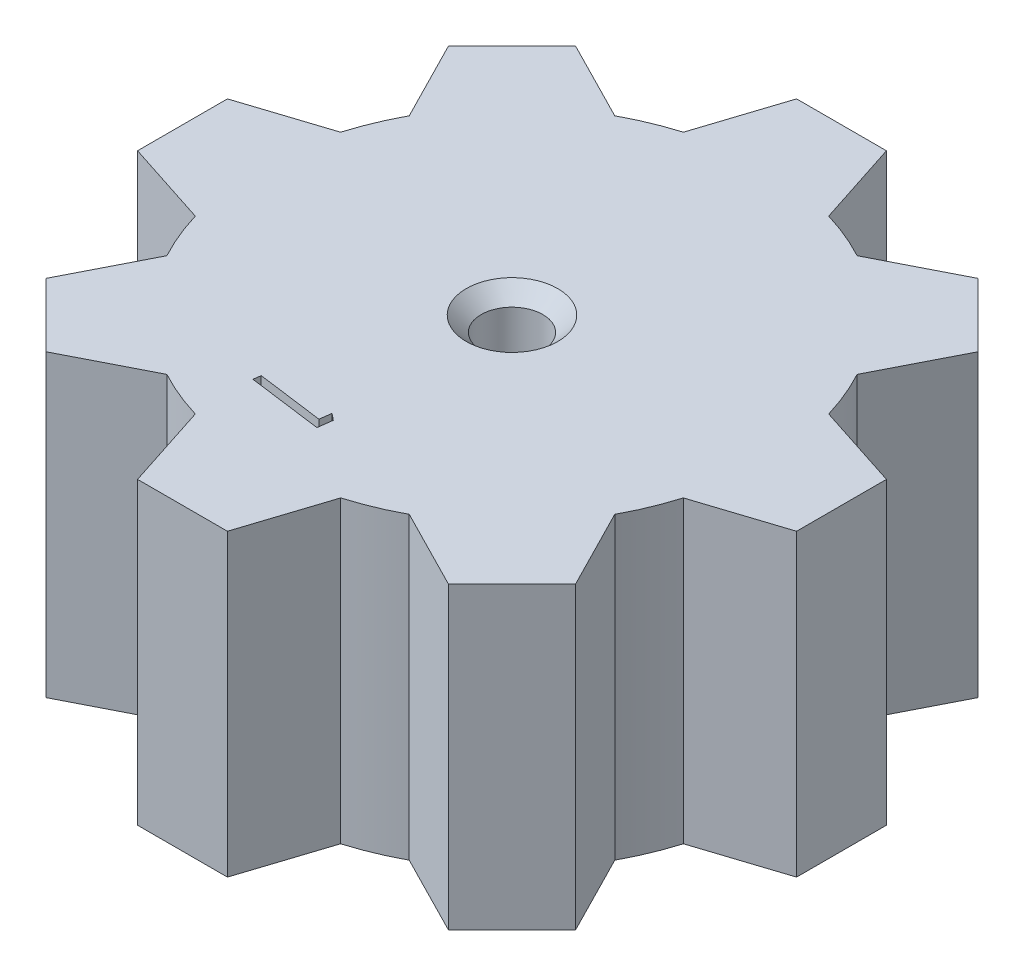
SolidWorks part; units mm, degrees
ref_plane "Front Plane" through (0, 0, 0) normal (0, 0, 1) x (1, 0, 0)
ref_plane "Top Plane" through (0, 0, 0) normal (0, 1, 0) x (1, 0, 0)
ref_plane "Right Plane" through (0, 0, 0) normal (1, 0, 0) x (0, 0, -1)
sketch "Sketch1" plane through (0, 0, 0) normal (0, 1, 0) x (1, 0, 0)
  line L1 (-0.25, 4.2426) -> (0.25, 4.2426) construction
  line L39 (0, 8.5) -> (0, 11) construction
  line L40 (-1.5, 11) -> (1.5, 11)
  line L41 (-1.5, 11) -> (-2.4259, 8.1465)
  line L42 (1.5, 11) -> (2.4259, 8.1465)
  line L43 (6.7175, 8.8388) -> (4.045, 7.4758)
  line L44 (6.7175, 8.8388) -> (8.8388, 6.7175)
  line L45 (8.8388, 6.7175) -> (7.4758, 4.045)
  line L46 (11, 1.5) -> (8.1465, 2.4259)
  line L47 (11, 1.5) -> (11, -1.5)
  line L48 (11, -1.5) -> (8.1465, -2.4259)
  line L49 (8.8388, -6.7175) -> (7.4758, -4.045)
  line L50 (8.8388, -6.7175) -> (6.7175, -8.8388)
  line L51 (6.7175, -8.8388) -> (4.045, -7.4758)
  line L52 (1.5, -11) -> (2.4259, -8.1465)
  line L53 (1.5, -11) -> (-1.5, -11)
  line L54 (-1.5, -11) -> (-2.4259, -8.1465)
  line L55 (-6.7175, -8.8388) -> (-4.045, -7.4758)
  line L56 (-6.7175, -8.8388) -> (-8.8388, -6.7175)
  line L57 (-8.8388, -6.7175) -> (-7.4758, -4.045)
  line L58 (-11, -1.5) -> (-8.1465, -2.4259)
  line L59 (-11, -1.5) -> (-11, 1.5)
  line L60 (-11, 1.5) -> (-8.1465, 2.4259)
  line L61 (-8.8388, 6.7175) -> (-7.4758, 4.045)
  line L62 (-8.8388, 6.7175) -> (-6.7175, 8.8388)
  line L63 (-6.7175, 8.8388) -> (-4.045, 7.4758)
  circle A0 centre (0, 0) radius 1.03
  circle A1 centre (0, 0) radius 5.25 construction
  circle A14 centre (0, 0) radius 8.5 construction
  arc A15 (2.4259, 8.1465) -> (4.045, 7.4758) centre (0, 0) cw
  arc A16 (7.4758, 4.045) -> (8.1465, 2.4259) centre (0, 0) cw
  arc A17 (8.1465, -2.4259) -> (7.4758, -4.045) centre (0, 0) cw
  arc A18 (4.045, -7.4758) -> (2.4259, -8.1465) centre (0, 0) cw
  arc A19 (-2.4259, -8.1465) -> (-4.045, -7.4758) centre (0, 0) cw
  arc A20 (-7.4758, -4.045) -> (-8.1465, -2.4259) centre (0, 0) cw
  arc A21 (-8.1465, 2.4259) -> (-7.4758, 4.045) centre (0, 0) cw
  arc A22 (-4.045, 7.4758) -> (-2.4259, 8.1465) centre (0, 0) cw
  point P31 (0, 0)
  point P60 (0, 0)
  point P71 (0, 11)
  point P105 (0, 0)
  dimension "D1" = 2.06
  dimension "D2" = 10.5
  dimension "D5" = 17
  dimension "D6" = 2.5
  dimension "D7" = 3
  dimension "D8" = 3
  dimension "D9" = 8
extrude "Boss-Extrude1" add sketch "Sketch1" along normal blind 10
sketch "Sketch2" plane through (0, 10, 0) normal (0, 1, 0) x (1, 0, 0)
  circle A0 centre (0, -6) radius 2.5 construction
  text T0 "1" font "Century Gothic" height 2.5
  dimension "D2" = 5
  dimension "D1" = 6
extrude "Cut-Extrude1" cut sketch "Sketch2" against normal blind 1
chamfer "Chamfer1" distance 0.5 angle 45 1 edges at (0, 10, 1.03)
